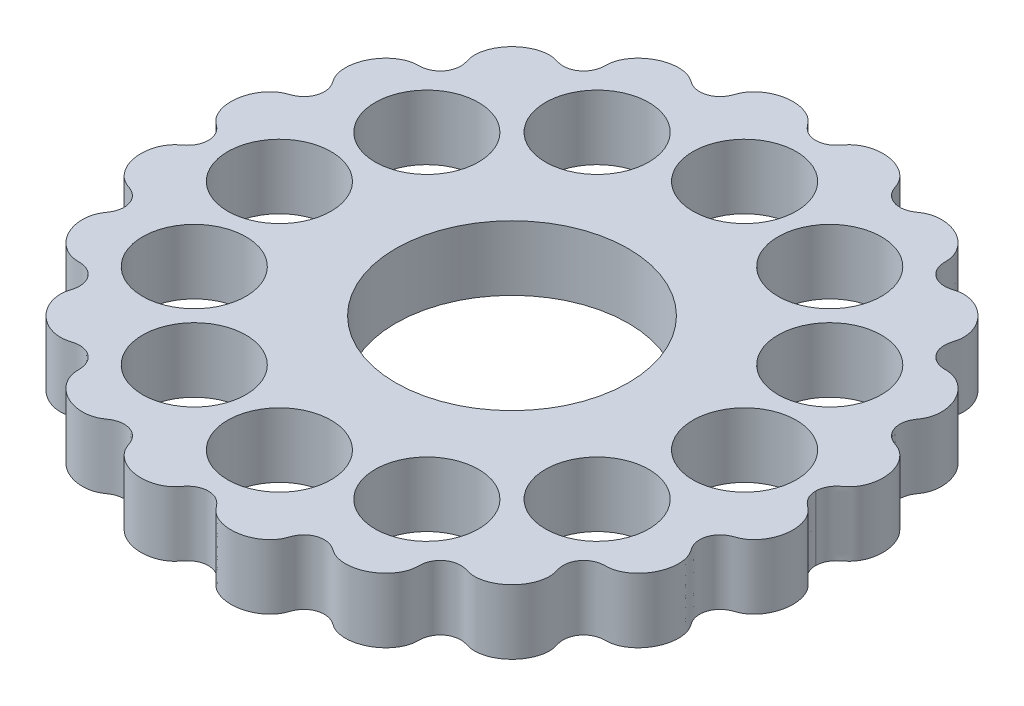
SolidWorks part; units mm, degrees
ref_plane "Front Plane" through (0, 0, 0) normal (0, 0, 1) x (1, 0, 0)
ref_plane "Top Plane" through (0, 0, 0) normal (0, 1, 0) x (1, 0, 0)
ref_plane "Right Plane" through (0, 0, 0) normal (1, 0, 0) x (0, 0, -1)
sketch "Sketch1" plane through (0, 0, 0) normal (0, 1, 0) x (1, 0, 0)
  line L0 (0, 0) -> (-50000, 0) construction
  line L1 (0, 0) -> (0, -50000) construction
  line L2 (23.5001, 0.0129) -> (23.5, 0)
  spline S0 degree 4 poles (21.8411, 12.6407) (22.0203, 12.5041) (22.35, 12.1932) (22.7473, 11.6384) (23.0173, 10.8905) (23.0906, 10.2173) (23.0371, 9.696) (22.9392, 9.3335) (22.8146, 9.0589) (22.692, 8.8679) (22.5629, 8.682) (22.419, 8.4431) (22.2854, 8.0962) (22.2414, 7.6218) (22.3709, 7.0968) (22.6485, 6.6795) (22.9702, 6.421) (23.2513, 6.2797) (23.4572, 6.2025) (23.6233, 6.1449) (23.8254, 6.0573) (24.0356, 5.9333) (24.2473, 5.7695) (24.502, 5.5171) (24.8314, 5.0866) (25.0873, 4.5396) (25.2302, 3.8953) (25.2334, 3.2499) (25.1572, 2.7564) (25.0153, 2.3299) (24.8302, 1.9758) (24.6224, 1.6961) (24.411, 1.4839) (24.1769, 1.3171) (23.9685, 1.1355) (23.7966, 0.9326) (23.6634, 0.7151) (23.5821, 0.5181) (23.5373, 0.3509) (23.5168, 0.2352) (23.5085, 0.1678) (23.5028, 0.0959) (23.4998, 0.0296) (23.4995, -0.0201) (23.5034, -0.114) (23.5136, -0.222) (23.531, -0.3171) (23.5554, -0.4164) (23.5855, -0.5129) (23.6209, -0.6076) (23.6842, -0.7456) (23.7985, -0.9357) (23.947, -1.1136) (24.1264, -1.2743) (24.3335, -1.4294) (24.5324, -1.5967) (24.7588, -1.8616) (24.9785, -2.239) (25.1878, -2.8156) (25.276, -3.602) (25.1512, -4.3864) (24.825, -5.1046) (24.4512, -5.5852) (24.1603, -5.8472) (23.9054, -6.0131) (23.7106, -6.1092) (23.5484, -6.1717) (23.3434, -6.2424) (23.1195, -6.3401) (22.8896, -6.4852) (22.6191, -6.7358) (22.3866, -7.0841) (22.2652, -7.485) (22.2642, -7.8967) (22.3323, -8.2005) (22.4106, -8.4063) (22.5009, -8.5801) (22.5924, -8.7259) (22.7163, -8.9012) (22.8496, -9.1231) (22.9784, -9.4447) (23.0662, -9.8699) (23.079, -10.3484) (23.0014, -10.8647) (22.7988, -11.4863) (22.4668, -12.0539) (22.0197, -12.5382) (21.5101, -12.8783) (21.1487, -13.0352) (20.8526, -13.1112) (20.6361, -13.1396) (20.4617, -13.1469) (20.2439, -13.1518) (19.9292, -13.1874) (19.5316, -13.3191) (19.1142, -13.6242) (18.8413, -14.0395) (18.7233, -14.4406) (18.7023, -14.7928) (18.731, -15.0474) (18.7862, -15.2675) (18.8561, -15.4948) (18.9091, -15.7274) (18.9298, -15.9928) (18.9132, -16.2851) (18.8535, -16.6269) (18.6921, -17.1381) (18.3245, -17.7837) (17.7439, -18.3557) (17.0924, -18.713) (16.5784, -18.8654) (16.2318, -18.9189) (15.9733, -18.9277) (15.7407, -18.9077) (15.5372, -18.8661) (15.3776, -18.8201) (15.1786, -18.7617) (14.943, -18.7144) (14.6698, -18.7015) (14.2938, -18.7551) (13.8912, -18.9202) (13.5591, -19.1968) (13.329, -19.5495) (13.2077, -19.8773) (13.1607, -20.1272) (13.1484, -20.3523) (13.1439, -20.5893) (13.1189, -20.8256) (13.0539, -21.0825) (12.9456, -21.3529) (12.7816, -21.6565) (12.4692, -22.0878) (11.918, -22.5852) (11.1862, -22.9469) (10.4524, -23.0817) (9.9115, -23.063) (9.5602, -23.002) (9.3067, -22.925) (9.0871, -22.8269) (8.8652, -22.6931) (8.6563, -22.5405) (8.4041, -22.4007) (8.1035, -22.3021) (7.7342, -22.2547) (7.3146, -22.3018) (6.9282, -22.4692) (6.6132, -22.7347) (6.426, -22.9803) (6.3196, -23.1695) (6.226, -23.3843) (6.1615, -23.5834) (6.0809, -23.7774) (5.9565, -23.9961) (5.784, -24.2355) (5.5184, -24.5091) (5.0388, -24.8605) (4.3152, -25.1707) (3.5217, -25.2796) (2.791, -25.1786) (2.2804, -24.9888) (1.9646, -24.8184) (1.7476, -24.6636) (1.57, -24.4991) (1.4301, -24.3329) (1.3258, -24.1944) (1.1879, -24.0267) (1.0116, -23.8555) (0.7865, -23.6977) (0.4445, -23.5448) (0.0278, -23.4694) (-0.3906, -23.5193) (-0.7681, -23.6831) (-1.0167, -23.8633) (-1.1726, -24.0123) (-1.2968, -24.1573) (-1.3971, -24.2895) (-1.5009, -24.4195) (-1.6153, -24.5403) (-1.7706, -24.6785) (-2.0089, -24.8488) (-2.3452, -25.0227) (-2.7867, -25.1648) (-3.2883, -25.2364) (-3.8051, -25.2271) (-4.3243, -25.1336) (-4.8311, -24.9525) (-5.2483, -24.7143) (-5.5687, -24.4567) (-5.8156, -24.1933) (-5.9728, -23.9761) (-6.0887, -23.762) (-6.1681, -23.5587) (-6.2249, -23.3939) (-6.3071, -23.1917) (-6.4261, -22.975) (-6.5967, -22.7573) (-6.8818, -22.5102) (-7.257, -22.3194) (-7.6664, -22.247) (-8.0669, -22.2913) (-8.3513, -22.3855) (-8.5443, -22.4795) (-8.7095, -22.5814) (-8.8513, -22.6808) (-9.0337, -22.7986) (-9.2686, -22.9122) (-9.5935, -23.0158) (-10.0105, -23.076) (-10.4681, -23.0671) (-10.9537, -22.977) (-11.5544, -22.765) (-12.1092, -22.4253) (-12.5378, -22.0129) (-12.8349, -21.57) (-12.9917, -21.2499) (-13.0792, -20.9957) (-13.1291, -20.7532) (-13.1456, -20.5281) (-13.1485, -20.348) (-13.1598, -20.1679) (-13.1871, -19.9893) (-13.2398, -19.7859) (-13.3301, -19.5635) (-13.5099, -19.2688) (-13.8217, -18.9659) (-14.2044, -18.7734) (-14.6123, -18.7018) (-14.9539, -18.7156) (-15.2392, -18.7725) (-15.5275, -18.8723) (-15.8439, -18.9245) (-16.211, -18.9262) (-16.6207, -18.8614) (-17.0591, -18.7152) (-17.5079, -18.4751) (-17.9196, -18.1609) (-18.2824, -17.7783) (-18.5826, -17.3336) (-18.777, -16.8971) (-18.8826, -16.5019) (-18.9258, -16.1458) (-18.9242, -15.8798) (-18.892, -15.6405) (-18.8254, -15.3899) (-18.7481, -15.1426) (-18.7014, -14.8514) (-18.7135, -14.5225) (-18.8073, -14.1364) (-18.9886, -13.8038) (-19.2393, -13.5373) (-19.5327, -13.3468) (-19.7706, -13.2423) (-20.0362, -13.1729) (-20.2842, -13.1482) (-20.5075, -13.1476) (-20.7449, -13.1288) (-20.9792, -13.0834) (-21.2878, -12.981) (-21.6535, -12.7906) (-22.1223, -12.4395) (-22.541, -11.9469) (-22.8516, -11.3681) (-23.0326, -10.7285) (-23.0802, -10.2504) (-23.0557, -9.8398) (-22.992, -9.529) (-22.9249, -9.3156) (-22.8467, -9.1329) (-22.7647, -8.9796) (-22.6446, -8.7988) (-22.4959, -8.5848) (-22.3648, -8.3186) (-22.2799, -7.9987) (-22.2576, -7.5993) (-22.3357, -7.227) (-22.4995, -6.8994) (-22.7252, -6.633) (-22.921, -6.4657) (-23.1192, -6.3437) (-23.3081, -6.2576) (-23.4795, -6.1951) (-23.6284, -6.1423) (-23.8097, -6.0641) (-24.0159, -5.9464) (-24.2743, -5.7519) (-24.5591, -5.4572) (-24.8912, -4.9791) (-25.1334, -4.3824) (-25.2472, -3.7364) (-25.2189, -3.0717) (-25.1135, -2.6002) (-24.9598, -2.2161) (-24.8002, -1.94) (-24.6679, -1.7581) (-24.5347, -1.6091) (-24.407, -1.4897) (-24.2694, -1.3823) (-24.1311, -1.2758) (-23.9675, -1.131) (-23.7997, -0.9408) (-23.6474, -0.695) (-23.5093, -0.3171) (-23.4729, 0.1074) (-23.5563, 0.5011) (-23.727, 0.8323) (-23.8894, 1.0456) (-24.0393, 1.199) (-24.2048, 1.3348) (-24.3765, 1.4623) (-24.5497, 1.6204) (-24.7146, 1.8141) (-24.8655, 2.0434) (-24.9966, 2.307) (-25.1232, 2.6524) (-25.2175, 3.0845) (-25.2518, 3.7039) (-25.1382, 4.3691) (-24.8937, 4.9741) (-24.5632, 5.452) (-24.2798, 5.7469) (-24.0225, 5.942) (-23.817, 6.0603) (-23.6362, 6.1392) (-23.4877, 6.1923) (-23.3164, 6.2542) (-23.1277, 6.3393) (-22.9293, 6.4598) (-22.733, 6.6253) (-22.5056, 6.8899) (-22.3394, 7.2164) (-22.2585, 7.5886) (-22.2783, 7.9889) (-22.3615, 8.31) (-22.4915, 8.5773) (-22.6398, 8.7922) (-22.7607, 8.9729) (-22.8435, 9.1261) (-22.9224, 9.3089) (-22.9904, 9.5224) (-23.0549, 9.8336) (-23.0804, 10.2449) (-23.0335, 10.724) (-22.8533, 11.364) (-22.5436, 11.943) (-22.1262, 12.4356) (-21.6591, 12.787) (-21.2947, 12.9779) (-20.9869, 13.0812) (-20.7533, 13.1275) (-20.5163, 13.1475) (-20.2934, 13.1479) (-20.0459, 13.1713) (-19.7806, 13.239) (-19.5426, 13.3415) (-19.248, 13.5298) (-18.9952, 13.7945) (-18.8114, 14.1263) (-18.7148, 14.5127) (-18.7008, 14.8421) (-18.7461, 15.1341) (-18.8228, 15.3821) (-18.8905, 15.6327) (-18.9237, 15.8723) (-18.9262, 16.1388) (-18.8839, 16.4957) (-18.779, 16.8918) (-18.585, 17.3295) (-18.285, 17.775) (-17.9228, 18.158) (-17.5119, 18.4724) (-17.0645, 18.7128) (-16.6274, 18.8596) (-16.2186, 18.9255) (-15.8523, 18.925) (-15.5361, 18.8747) (-15.2483, 18.7754) (-14.9641, 18.7169) (-14.6885, 18.7041) (-14.4289, 18.7338) (-14.0921, 18.8296) (-13.7745, 19.0104) (-13.5041, 19.274) (-13.301, 19.6135) (-13.1922, 19.9226) (-13.1499, 20.2133) (-13.1483, 20.4715) (-13.132, 20.7294) (-13.0869, 20.9657) (-13.0047, 21.2177) (-12.8523, 21.5409) (-12.5546, 21.9954) (-12.1223, 22.4164) (-11.5626, 22.7616) (-10.9582, 22.9757) (-10.4739, 23.0664) (-10.0172, 23.0763) (-9.601, 23.0174) (-9.2764, 22.9152) (-9.0416, 22.8028) (-8.859, 22.6861) (-8.7175, 22.5869) (-8.5532, 22.4845) (-8.3612, 22.3896) (-8.078, 22.2937) (-7.674, 22.246) (-7.258, 22.3178) (-6.875, 22.5132) (-6.5834, 22.7704) (-6.4109, 22.9973) (-6.2922, 23.2227) (-6.2111, 23.4323) (-6.1528, 23.6021) (-6.0658, 23.8096) (-5.9421, 24.0229) (-5.7795, 24.2358) (-5.5311, 24.4893) (-5.1118, 24.8155) (-4.5772, 25.0729) (-3.9447, 25.2227) (-3.3073, 25.2369) (-2.8158, 25.1705) (-2.3764, 25.0349) (-2.0369, 24.8654) (-1.7916, 24.6954) (-1.6273, 24.5522) (-1.5064, 24.4263) (-1.3975, 24.2901) (-1.2923, 24.1513) (-1.1647, 24.0039) (-1.0077, 23.8561) (-0.7627, 23.6813) (-0.3926, 23.5208) (0.0198, 23.4698) (0.4337, 23.5415) (0.7775, 23.6926) (1.004, 23.8492) (1.1816, 24.0198) (1.3204, 24.1873) (1.4248, 24.3261) (1.5642, 24.4931) (1.7414, 24.6587) (1.9584, 24.8145) (2.2742, 24.9862) (2.7855, 25.1775) (3.3895, 25.262) (4.055, 25.2066) (4.6806, 25.0138) (5.1366, 24.7881) (5.5131, 24.5135) (5.7789, 24.2413) (5.9519, 24.0032) (6.0559, 23.8218) (6.1261, 23.67) (6.1838, 23.513) (6.2393, 23.3556) (6.3148, 23.1792) (6.4198, 22.9898) (6.6049, 22.7433) (6.9178, 22.4755) (7.303, 22.305) (7.7226, 22.2547) (8.093, 22.2996) (8.3949, 22.3966) (8.6484, 22.5353) (8.8579, 22.6879) (9.0795, 22.8231) (9.2992, 22.9222) (9.5529, 23.0003) (9.9047, 23.0624) (10.4468, 23.0824) (11.0445, 22.9736) (11.6583, 22.7131) (12.1928, 22.3338) (12.5572, 21.9739) (12.8297, 21.592) (12.9966, 21.2469) (13.0848, 20.9637) (13.1336, 20.7153) (13.1478, 20.5046) (13.1482, 20.294) (13.1736, 20.0598) (13.2193, 19.8467) (13.3262, 19.5558) (13.553, 19.204) (13.882, 18.926) (14.2829, 18.7581) (14.6594, 18.702) (14.9333, 18.7133) (15.1696, 18.7594) (15.3691, 18.8175) (15.5288, 18.864) (15.7325, 18.9066) (15.9654, 18.9275) (16.2245, 18.9196) (16.5719, 18.867) (17.0874, 18.7154) (17.7398, 18.3589) (18.3213, 17.7878) (18.723, 17.0846) (18.8921, 16.4922) (18.9349, 16.0672) (18.9101, 15.7355) (18.8584, 15.5029) (18.7887, 15.2759) (18.7327, 15.0564) (18.7027, 14.8026) (18.7215, 14.4513) (18.8364, 14.05) (19.0669, 13.6933) (19.3919, 13.4205) (19.7259, 13.2551) (19.9902, 13.1813) (20.2348, 13.1524) (20.453, 13.147) (20.6277, 13.1403) (20.8446, 13.1128) (21.0781, 13.0539) (21.323, 12.9597) (21.6321, 12.7968) (22.0604, 12.4936) (22.553, 11.9616) (22.9181, 11.2563) (23.0818, 10.4848) (23.0669, 9.8769) (22.9806, 9.4523) (22.8531, 9.1307) (22.7213, 8.9085) (22.5727, 8.6983) (22.4484, 8.4944) (22.345, 8.2523) (22.2654, 7.9078) (22.2634, 7.4966) (22.3817, 7.0947) (22.6119, 6.7443) (22.8815, 6.4913) (23.1111, 6.3446) (23.335, 6.2456) (23.5402, 6.1745) (23.7028, 6.1126) (23.8984, 6.0172) (24.0996, 5.8873) (24.3006, 5.721) (24.5407, 5.4699) (24.7723, 5.1549) (24.9858, 4.7511) (25.1917, 4.1307) (25.2613, 3.4766) (25.1888, 2.8213) (24.9813, 2.2454) (24.7632, 1.8681) (24.5382, 1.6028) (24.3405, 1.4347) (24.1336, 1.2799) (23.9537, 1.1206) (23.8045, 0.9437) (23.6893, 0.7551) (23.6182, 0.6024) (23.5719, 0.4769) (23.5365, 0.3449) (23.5154, 0.2341) (23.5044, 0.1265) (23.4997, 0.0329) (23.4996, -0.0168) (23.502, -0.0831) (23.5072, -0.1552) (23.515, -0.2227) (23.5345, -0.3385) (23.578, -0.5062) (23.6578, -0.7037) (23.7892, -0.9224) (23.9596, -1.1262) (24.1387, -1.2851) (24.3097, -1.411) (24.481, -1.5549) (24.6365, -1.7161) (24.8235, -1.9651) (25.0104, -2.318) (25.1542, -2.744) (25.2324, -3.237) (25.2318, -3.8869) (25.0888, -4.5381) (24.8293, -5.0922) (24.4927, -5.5283) (24.2365, -5.7788) (24.0277, -5.9382) (23.8244, -6.0571) (23.6336, -6.1406) (23.4767, -6.1959) (23.2814, -6.2675) (23.002, -6.4009) (22.6719, -6.6524) (22.3818, -7.0679) (22.2423, -7.6006) (22.2819, -8.0803) (22.4122, -8.4287) (22.5543, -8.6688) (22.683, -8.8553) (22.8074, -9.0452) (22.9106, -9.2684) (22.9897, -9.5192) (23.0486, -9.8124) (23.0852, -10.2583) (23.0208, -10.8762) (22.7541, -11.6255) (22.359, -12.1823) (22.0307, -12.4947) (21.8521, -12.6323) knots 0 0 0 0 0 0.004253 0.008505 0.012712 0.014816 0.01692 0.018344 0.019769 0.020481 0.021194 0.022619 0.025024 0.027429 0.030028 0.032627 0.034286 0.035116 0.035945 0.036775 0.037604 0.039264 0.040537 0.041811 0.044358 0.049452 0.051797 0.054142 0.056487 0.058832 0.060238 0.061643 0.063049 0.064455 0.065652 0.06685 0.068047 0.069245 0.069666 0.070088 0.070299 0.07051 0.070932 0.07125 0.071568 0.072204 0.072839 0.073157 0.073475 0.074111 0.074747 0.076018 0.077648 0.078462 0.079277 0.080906 0.082536 0.085004 0.087473 0.09241 0.097302 0.099748 0.102194 0.103832 0.104651 0.105469 0.106288 0.107107 0.108745 0.110067 0.111388 0.114031 0.11655 0.11781 0.11907 0.119881 0.120692 0.121503 0.122314 0.123936 0.125558 0.12801 0.130462 0.132915 0.135367 0.14029 0.142752 0.145214 0.146859 0.147682 0.148505 0.149327 0.15015 0.151796 0.154462 0.157129 0.159695 0.160978 0.16226 0.163757 0.164505 0.165254 0.16675 0.168247 0.169507 0.170766 0.173285 0.178324 0.183363 0.185882 0.187142 0.188402 0.189968 0.190751 0.191534 0.192317 0.1931 0.194666 0.196057 0.197447 0.200228 0.202766 0.204035 0.205304 0.206795 0.20754 0.208286 0.209777 0.211268 0.212519 0.213771 0.216275 0.221281 0.226368 0.228911 0.230183 0.231455 0.233082 0.233896 0.234709 0.236336 0.237964 0.239304 0.240644 0.243325 0.245831 0.247083 0.248336 0.249126 0.249917 0.251497 0.252287 0.253078 0.254658 0.257053 0.259448 0.264238 0.269357 0.271917 0.273197 0.274477 0.276114 0.276932 0.277751 0.278569 0.279388 0.281025 0.282374 0.283723 0.28642 0.288913 0.290159 0.291406 0.29219 0.292973 0.293757 0.294541 0.295325 0.296109 0.297676 0.300056 0.302435 0.304815 0.307195 0.30977 0.312346 0.314922 0.31621 0.317498 0.319143 0.319966 0.320789 0.321612 0.322434 0.32408 0.325438 0.326797 0.329514 0.331921 0.333124 0.334327 0.335145 0.335963 0.336781 0.337599 0.339235 0.340871 0.343191 0.345511 0.347831 0.350151 0.355163 0.35767 0.358923 0.360176 0.361877 0.362727 0.363578 0.364428 0.365279 0.366129 0.36698 0.368387 0.369793 0.372606 0.375067 0.376297 0.377527 0.379032 0.380537 0.382042 0.383547 0.385937 0.388327 0.390718 0.393108 0.39567 0.398233 0.400795 0.402076 0.403357 0.404987 0.405802 0.406616 0.408246 0.409875 0.411331 0.412786 0.415696 0.416917 0.418138 0.419358 0.420579 0.422076 0.422824 0.423573 0.425069 0.426566 0.428941 0.431316 0.436065 0.438642 0.441219 0.443796 0.445084 0.446372 0.447191 0.44801 0.448829 0.449649 0.451287 0.452925 0.45439 0.455855 0.458784 0.459995 0.461205 0.462415 0.463625 0.46437 0.465114 0.465859 0.466604 0.468093 0.469583 0.471943 0.474303 0.479023 0.481613 0.484204 0.486795 0.48809 0.489385 0.490209 0.491032 0.491856 0.492679 0.493503 0.494326 0.495974 0.497448 0.498922 0.50187 0.503888 0.504897 0.505906 0.506915 0.507924 0.508933 0.509942 0.511328 0.512713 0.514099 0.515485 0.518256 0.521028 0.525738 0.528093 0.530448 0.531936 0.533423 0.534167 0.534911 0.535654 0.536398 0.537605 0.538811 0.540018 0.541224 0.54416 0.545628 0.547096 0.548737 0.550378 0.551198 0.552019 0.552839 0.55366 0.55495 0.556241 0.558822 0.561404 0.563985 0.568725 0.571095 0.573465 0.574959 0.576453 0.577201 0.577948 0.579442 0.580659 0.581877 0.583094 0.584311 0.587228 0.588687 0.590145 0.591777 0.59341 0.594226 0.595042 0.596674 0.597958 0.599241 0.601808 0.604375 0.606942 0.609328 0.611713 0.614098 0.616483 0.617986 0.619488 0.62099 0.622492 0.623719 0.624946 0.626174 0.627401 0.630298 0.631746 0.633195 0.634819 0.636442 0.637254 0.638066 0.63969 0.640967 0.642243 0.644795 0.6499 0.652215 0.65453 0.656845 0.659161 0.660793 0.662425 0.663242 0.664058 0.664874 0.66569 0.666891 0.668091 0.670492 0.673292 0.674692 0.676091 0.677787 0.678634 0.679482 0.680329 0.681177 0.682872 0.68412 0.685368 0.687864 0.692856 0.695186 0.697517 0.699847 0.702177 0.703821 0.704643 0.705464 0.706286 0.707108 0.70793 0.708752 0.70996 0.711169 0.713586 0.71629 0.717642 0.718994 0.720633 0.721453 0.722273 0.723093 0.723913 0.725553 0.726835 0.728118 0.730683 0.735813 0.738203 0.740593 0.742983 0.745373 0.746949 0.747737 0.748525 0.749313 0.750101 0.750889 0.751677 0.752928 0.754179 0.756681 0.759367 0.76071 0.762053 0.763683 0.765314 0.766129 0.766944 0.768574 0.769849 0.771123 0.773672 0.778769 0.781175 0.78358 0.785985 0.788391 0.789981 0.790776 0.791571 0.793161 0.793956 0.794751 0.796007 0.797264 0.799777 0.802564 0.803958 0.805352 0.806921 0.807705 0.80849 0.809274 0.810059 0.811628 0.81289 0.814152 0.816677 0.821726 0.826754 0.829268 0.831782 0.833277 0.834772 0.835519 0.836267 0.837761 0.83904 0.840318 0.842875 0.845549 0.846886 0.848223 0.849872 0.850696 0.85152 0.852344 0.853168 0.854816 0.856049 0.857283 0.859749 0.864683 0.869577 0.872024 0.874471 0.876091 0.87771 0.87852 0.87933 0.88095 0.882206 0.883462 0.885973 0.888624 0.889949 0.891274 0.892915 0.893735 0.894555 0.895375 0.896195 0.897836 0.899061 0.900287 0.902738 0.905189 0.90764 0.912566 0.91503 0.917493 0.91912 0.920747 0.92156 0.922374 0.924001 0.925269 0.925903 0.926536 0.92717 0.927804 0.928438 0.928755 0.929072 0.929494 0.929706 0.929917 0.930339 0.930762 0.931959 0.933156 0.934353 0.93555 0.936956 0.937659 0.938362 0.939767 0.941173 0.943518 0.945863 0.948208 0.950553 0.955729 0.958318 0.959612 0.960906 0.962476 0.96326 0.964045 0.96483 0.965615 0.967185 0.969873 0.972561 0.974966 0.977371 0.978797 0.97951 0.980223 0.981649 0.983075 0.984127 0.985179 0.987283 0.991492 0.995746 1 1 1 1 1 construction
  spline S1 degree 4 poles (23.5, 0) (23.5, -0.0145) (23.5005, -0.0435) (23.5034, -0.114) (23.5136, -0.222) (23.531, -0.3171) (23.5554, -0.4164) (23.5855, -0.5129) (23.6209, -0.6076) (23.6842, -0.7456) (23.7985, -0.9357) (23.947, -1.1136) (24.1264, -1.2743) (24.3335, -1.4294) (24.5324, -1.5967) (24.7588, -1.8616) (24.9785, -2.239) (25.1878, -2.8156) (25.276, -3.602) (25.1512, -4.3864) (24.825, -5.1046) (24.4512, -5.5852) (24.1603, -5.8472) (23.9054, -6.0131) (23.7106, -6.1092) (23.5484, -6.1717) (23.3434, -6.2424) (23.1195, -6.3401) (22.8896, -6.4852) (22.6191, -6.7358) (22.3866, -7.0841) (22.2652, -7.485) (22.2642, -7.8967) (22.3323, -8.2005) (22.4106, -8.4063) (22.5009, -8.5801) (22.5924, -8.7259) (22.7163, -8.9012) (22.8496, -9.1231) (22.9784, -9.4447) (23.0662, -9.8699) (23.079, -10.3484) (23.0014, -10.8647) (22.7988, -11.4863) (22.4668, -12.0539) (22.0197, -12.5382) (21.5101, -12.8783) (21.1487, -13.0352) (20.8526, -13.1112) (20.6361, -13.1396) (20.4617, -13.1469) (20.2439, -13.1518) (19.9292, -13.1874) (19.5316, -13.3191) (19.1142, -13.6242) (18.8413, -14.0395) (18.7233, -14.4406) (18.7023, -14.7928) (18.731, -15.0474) (18.7862, -15.2675) (18.8561, -15.4948) (18.9091, -15.7274) (18.9298, -15.9928) (18.9132, -16.2851) (18.8535, -16.6269) (18.6921, -17.1381) (18.3245, -17.7837) (17.7439, -18.3557) (17.0924, -18.713) (16.5784, -18.8654) (16.2318, -18.9189) (15.9733, -18.9277) (15.7407, -18.9077) (15.5372, -18.8661) (15.3776, -18.8201) (15.1786, -18.7617) (14.943, -18.7144) (14.6698, -18.7015) (14.2938, -18.7551) (13.8912, -18.9202) (13.5591, -19.1968) (13.329, -19.5495) (13.2077, -19.8773) (13.1607, -20.1272) (13.1484, -20.3523) (13.1439, -20.5893) (13.1189, -20.8256) (13.0539, -21.0825) (12.9456, -21.3529) (12.7816, -21.6565) (12.4692, -22.0878) (11.918, -22.5852) (11.1862, -22.9469) (10.4524, -23.0817) (9.9115, -23.063) (9.5602, -23.002) (9.3067, -22.925) (9.0871, -22.8269) (8.8652, -22.6931) (8.6563, -22.5405) (8.4041, -22.4007) (8.1035, -22.3021) (7.7342, -22.2547) (7.3146, -22.3018) (6.9282, -22.4692) (6.6132, -22.7347) (6.426, -22.9803) (6.3196, -23.1695) (6.226, -23.3843) (6.1615, -23.5834) (6.0809, -23.7774) (5.9565, -23.9961) (5.784, -24.2355) (5.5184, -24.5091) (5.0388, -24.8605) (4.3152, -25.1707) (3.5217, -25.2796) (2.791, -25.1786) (2.2804, -24.9888) (1.9646, -24.8184) (1.7476, -24.6636) (1.57, -24.4991) (1.4301, -24.3329) (1.3258, -24.1944) (1.1879, -24.0267) (1.0116, -23.8555) (0.7865, -23.6977) (0.4445, -23.5448) (0.0278, -23.4694) (-0.3906, -23.5193) (-0.7681, -23.6831) (-1.0167, -23.8633) (-1.1726, -24.0123) (-1.2968, -24.1573) (-1.3971, -24.2895) (-1.5009, -24.4195) (-1.6153, -24.5403) (-1.7706, -24.6785) (-2.0089, -24.8488) (-2.3452, -25.0227) (-2.7867, -25.1648) (-3.2883, -25.2364) (-3.8051, -25.2271) (-4.3243, -25.1336) (-4.8311, -24.9525) (-5.2483, -24.7143) (-5.5687, -24.4567) (-5.8156, -24.1933) (-5.9728, -23.9761) (-6.0887, -23.762) (-6.1681, -23.5587) (-6.2249, -23.3939) (-6.3071, -23.1917) (-6.4261, -22.975) (-6.5967, -22.7573) (-6.8818, -22.5102) (-7.257, -22.3194) (-7.6664, -22.247) (-8.0669, -22.2913) (-8.3513, -22.3855) (-8.5443, -22.4795) (-8.7095, -22.5814) (-8.8513, -22.6808) (-9.0337, -22.7986) (-9.2686, -22.9122) (-9.5935, -23.0158) (-10.0105, -23.076) (-10.4681, -23.0671) (-10.9537, -22.977) (-11.5544, -22.765) (-12.1092, -22.4253) (-12.5378, -22.0129) (-12.8349, -21.57) (-12.9917, -21.2499) (-13.0792, -20.9957) (-13.1291, -20.7532) (-13.1456, -20.5281) (-13.1485, -20.348) (-13.1598, -20.1679) (-13.1871, -19.9893) (-13.2398, -19.7859) (-13.3301, -19.5635) (-13.5099, -19.2688) (-13.8217, -18.9659) (-14.2044, -18.7734) (-14.6123, -18.7018) (-14.9539, -18.7156) (-15.2392, -18.7725) (-15.5275, -18.8723) (-15.8439, -18.9245) (-16.211, -18.9262) (-16.6207, -18.8614) (-17.0591, -18.7152) (-17.5079, -18.4751) (-17.9196, -18.1609) (-18.2824, -17.7783) (-18.5826, -17.3336) (-18.777, -16.8971) (-18.8826, -16.5019) (-18.9258, -16.1458) (-18.9242, -15.8798) (-18.892, -15.6405) (-18.8254, -15.3899) (-18.7481, -15.1426) (-18.7014, -14.8514) (-18.7135, -14.5225) (-18.8073, -14.1364) (-18.9886, -13.8038) (-19.2393, -13.5373) (-19.5327, -13.3468) (-19.7706, -13.2423) (-20.0362, -13.1729) (-20.2842, -13.1482) (-20.5075, -13.1476) (-20.7449, -13.1288) (-20.9792, -13.0834) (-21.2878, -12.981) (-21.6535, -12.7906) (-22.1223, -12.4395) (-22.541, -11.9469) (-22.8516, -11.3681) (-23.0326, -10.7285) (-23.0802, -10.2504) (-23.0557, -9.8398) (-22.992, -9.529) (-22.9249, -9.3156) (-22.8467, -9.1329) (-22.7647, -8.9796) (-22.6446, -8.7988) (-22.4959, -8.5848) (-22.3648, -8.3186) (-22.2799, -7.9987) (-22.2576, -7.5993) (-22.3357, -7.227) (-22.4995, -6.8994) (-22.7252, -6.633) (-22.921, -6.4657) (-23.1192, -6.3437) (-23.3081, -6.2576) (-23.4795, -6.1951) (-23.6284, -6.1423) (-23.8097, -6.0641) (-24.0159, -5.9464) (-24.2743, -5.7519) (-24.5591, -5.4572) (-24.8912, -4.9791) (-25.1334, -4.3824) (-25.2472, -3.7364) (-25.2189, -3.0717) (-25.1135, -2.6002) (-24.9598, -2.2161) (-24.8002, -1.94) (-24.6679, -1.7581) (-24.5347, -1.6091) (-24.407, -1.4897) (-24.2694, -1.3823) (-24.1311, -1.2758) (-23.9675, -1.131) (-23.7997, -0.9408) (-23.6474, -0.695) (-23.5093, -0.3171) (-23.4729, 0.1074) (-23.5563, 0.5011) (-23.727, 0.8323) (-23.8894, 1.0456) (-24.0393, 1.199) (-24.2048, 1.3348) (-24.3765, 1.4623) (-24.5497, 1.6204) (-24.7146, 1.8141) (-24.8655, 2.0434) (-24.9966, 2.307) (-25.1232, 2.6524) (-25.2175, 3.0845) (-25.2518, 3.7039) (-25.1382, 4.3691) (-24.8937, 4.9741) (-24.5632, 5.452) (-24.2798, 5.7469) (-24.0225, 5.942) (-23.817, 6.0603) (-23.6362, 6.1392) (-23.4877, 6.1923) (-23.3164, 6.2542) (-23.1277, 6.3393) (-22.9293, 6.4598) (-22.733, 6.6253) (-22.5056, 6.8899) (-22.3394, 7.2164) (-22.2585, 7.5886) (-22.2783, 7.9889) (-22.3615, 8.31) (-22.4915, 8.5773) (-22.6398, 8.7922) (-22.7607, 8.9729) (-22.8435, 9.1261) (-22.9224, 9.3089) (-22.9904, 9.5224) (-23.0549, 9.8336) (-23.0804, 10.2449) (-23.0335, 10.724) (-22.8533, 11.364) (-22.5436, 11.943) (-22.1262, 12.4356) (-21.6591, 12.787) (-21.2947, 12.9779) (-20.9869, 13.0812) (-20.7533, 13.1275) (-20.5163, 13.1475) (-20.2934, 13.1479) (-20.0459, 13.1713) (-19.7806, 13.239) (-19.5426, 13.3415) (-19.248, 13.5298) (-18.9952, 13.7945) (-18.8114, 14.1263) (-18.7148, 14.5127) (-18.7008, 14.8421) (-18.7461, 15.1341) (-18.8228, 15.3821) (-18.8905, 15.6327) (-18.9237, 15.8723) (-18.9262, 16.1388) (-18.8839, 16.4957) (-18.779, 16.8918) (-18.585, 17.3295) (-18.285, 17.775) (-17.9228, 18.158) (-17.5119, 18.4724) (-17.0645, 18.7128) (-16.6274, 18.8596) (-16.2186, 18.9255) (-15.8523, 18.925) (-15.5361, 18.8747) (-15.2483, 18.7754) (-14.9641, 18.7169) (-14.6885, 18.7041) (-14.4289, 18.7338) (-14.0921, 18.8296) (-13.7745, 19.0104) (-13.5041, 19.274) (-13.301, 19.6135) (-13.1922, 19.9226) (-13.1499, 20.2133) (-13.1483, 20.4715) (-13.132, 20.7294) (-13.0869, 20.9657) (-13.0047, 21.2177) (-12.8523, 21.5409) (-12.5546, 21.9954) (-12.1223, 22.4164) (-11.5626, 22.7616) (-10.9582, 22.9757) (-10.4739, 23.0664) (-10.0172, 23.0763) (-9.601, 23.0174) (-9.2764, 22.9152) (-9.0416, 22.8028) (-8.859, 22.6861) (-8.7175, 22.5869) (-8.5532, 22.4845) (-8.3612, 22.3896) (-8.078, 22.2937) (-7.674, 22.246) (-7.258, 22.3178) (-6.875, 22.5132) (-6.5834, 22.7704) (-6.4109, 22.9973) (-6.2922, 23.2227) (-6.2111, 23.4323) (-6.1528, 23.6021) (-6.0658, 23.8096) (-5.9421, 24.0229) (-5.7795, 24.2358) (-5.5311, 24.4893) (-5.1118, 24.8155) (-4.5772, 25.0729) (-3.9447, 25.2227) (-3.3073, 25.2369) (-2.8158, 25.1705) (-2.3764, 25.0349) (-2.0369, 24.8654) (-1.7916, 24.6954) (-1.6273, 24.5522) (-1.5064, 24.4263) (-1.3975, 24.2901) (-1.2923, 24.1513) (-1.1647, 24.0039) (-1.0077, 23.8561) (-0.7627, 23.6813) (-0.3926, 23.5208) (0.0198, 23.4698) (0.4337, 23.5415) (0.7775, 23.6926) (1.004, 23.8492) (1.1816, 24.0198) (1.3204, 24.1873) (1.4248, 24.3261) (1.5642, 24.4931) (1.7414, 24.6587) (1.9584, 24.8145) (2.2742, 24.9862) (2.7855, 25.1775) (3.3895, 25.262) (4.055, 25.2066) (4.6806, 25.0138) (5.1366, 24.7881) (5.5131, 24.5135) (5.7789, 24.2413) (5.9519, 24.0032) (6.0559, 23.8218) (6.1261, 23.67) (6.1838, 23.513) (6.2393, 23.3556) (6.3148, 23.1792) (6.4198, 22.9898) (6.6049, 22.7433) (6.9178, 22.4755) (7.303, 22.305) (7.7226, 22.2547) (8.093, 22.2996) (8.3949, 22.3966) (8.6484, 22.5353) (8.8579, 22.6879) (9.0795, 22.8231) (9.2992, 22.9222) (9.5529, 23.0003) (9.9047, 23.0624) (10.4468, 23.0824) (11.0445, 22.9736) (11.6583, 22.7131) (12.1928, 22.3338) (12.5572, 21.9739) (12.8297, 21.592) (12.9966, 21.2469) (13.0848, 20.9637) (13.1336, 20.7153) (13.1478, 20.5046) (13.1482, 20.294) (13.1736, 20.0598) (13.2193, 19.8467) (13.3262, 19.5558) (13.553, 19.204) (13.882, 18.926) (14.2829, 18.7581) (14.6594, 18.702) (14.9333, 18.7133) (15.1696, 18.7594) (15.3691, 18.8175) (15.5288, 18.864) (15.7325, 18.9066) (15.9654, 18.9275) (16.2245, 18.9196) (16.5719, 18.867) (17.0874, 18.7154) (17.7398, 18.3589) (18.3213, 17.7878) (18.723, 17.0846) (18.8921, 16.4922) (18.9349, 16.0672) (18.9101, 15.7355) (18.8584, 15.5029) (18.7887, 15.2759) (18.7327, 15.0564) (18.7027, 14.8026) (18.7215, 14.4513) (18.8364, 14.05) (19.0669, 13.6933) (19.3919, 13.4205) (19.7259, 13.2551) (19.9902, 13.1813) (20.2348, 13.1524) (20.453, 13.147) (20.6277, 13.1403) (20.8446, 13.1128) (21.0781, 13.0539) (21.323, 12.9597) (21.6321, 12.7968) (22.0604, 12.4936) (22.553, 11.9616) (22.9181, 11.2563) (23.0818, 10.4848) (23.0669, 9.8769) (22.9806, 9.4523) (22.8531, 9.1307) (22.7213, 8.9085) (22.5727, 8.6983) (22.4484, 8.4944) (22.345, 8.2523) (22.2654, 7.9078) (22.2634, 7.4966) (22.3817, 7.0947) (22.6119, 6.7443) (22.8815, 6.4913) (23.1111, 6.3446) (23.335, 6.2456) (23.5402, 6.1745) (23.7028, 6.1126) (23.8984, 6.0172) (24.0996, 5.8873) (24.3006, 5.721) (24.5407, 5.4699) (24.7723, 5.1549) (24.9858, 4.7511) (25.1917, 4.1307) (25.2613, 3.4766) (25.1888, 2.8213) (24.9813, 2.2454) (24.7632, 1.8681) (24.5382, 1.6028) (24.3405, 1.4347) (24.1336, 1.2799) (23.9537, 1.1206) (23.8045, 0.9437) (23.6893, 0.7551) (23.6182, 0.6024) (23.5719, 0.4769) (23.5365, 0.3449) (23.5154, 0.2341) (23.5044, 0.1265) (23.5009, 0.0563) (23.5002, 0.0274) (23.5001, 0.0129) knots 0.070932 0.070932 0.070932 0.070932 0.070932 0.07125 0.071568 0.072204 0.072839 0.073157 0.073475 0.074111 0.074747 0.076018 0.077648 0.078462 0.079277 0.080906 0.082536 0.085004 0.087473 0.09241 0.097302 0.099748 0.102194 0.103832 0.104651 0.105469 0.106288 0.107107 0.108745 0.110067 0.111388 0.114031 0.11655 0.11781 0.11907 0.119881 0.120692 0.121503 0.122314 0.123936 0.125558 0.12801 0.130462 0.132915 0.135367 0.14029 0.142752 0.145214 0.146859 0.147682 0.148505 0.149327 0.15015 0.151796 0.154462 0.157129 0.159695 0.160978 0.16226 0.163757 0.164505 0.165254 0.16675 0.168247 0.169507 0.170766 0.173285 0.178324 0.183363 0.185882 0.187142 0.188402 0.189968 0.190751 0.191534 0.192317 0.1931 0.194666 0.196057 0.197447 0.200228 0.202766 0.204035 0.205304 0.206795 0.20754 0.208286 0.209777 0.211268 0.212519 0.213771 0.216275 0.221281 0.226368 0.228911 0.230183 0.231455 0.233082 0.233896 0.234709 0.236336 0.237964 0.239304 0.240644 0.243325 0.245831 0.247083 0.248336 0.249126 0.249917 0.251497 0.252287 0.253078 0.254658 0.257053 0.259448 0.264238 0.269357 0.271917 0.273197 0.274477 0.276114 0.276932 0.277751 0.278569 0.279388 0.281025 0.282374 0.283723 0.28642 0.288913 0.290159 0.291406 0.29219 0.292973 0.293757 0.294541 0.295325 0.296109 0.297676 0.300056 0.302435 0.304815 0.307195 0.30977 0.312346 0.314922 0.31621 0.317498 0.319143 0.319966 0.320789 0.321612 0.322434 0.32408 0.325438 0.326797 0.329514 0.331921 0.333124 0.334327 0.335145 0.335963 0.336781 0.337599 0.339235 0.340871 0.343191 0.345511 0.347831 0.350151 0.355163 0.35767 0.358923 0.360176 0.361877 0.362727 0.363578 0.364428 0.365279 0.366129 0.36698 0.368387 0.369793 0.372606 0.375067 0.376297 0.377527 0.379032 0.380537 0.382042 0.383547 0.385937 0.388327 0.390718 0.393108 0.39567 0.398233 0.400795 0.402076 0.403357 0.404987 0.405802 0.406616 0.408246 0.409875 0.411331 0.412786 0.415696 0.416917 0.418138 0.419358 0.420579 0.422076 0.422824 0.423573 0.425069 0.426566 0.428941 0.431316 0.436065 0.438642 0.441219 0.443796 0.445084 0.446372 0.447191 0.44801 0.448829 0.449649 0.451287 0.452925 0.45439 0.455855 0.458784 0.459995 0.461205 0.462415 0.463625 0.46437 0.465114 0.465859 0.466604 0.468093 0.469583 0.471943 0.474303 0.479023 0.481613 0.484204 0.486795 0.48809 0.489385 0.490209 0.491032 0.491856 0.492679 0.493503 0.494326 0.495974 0.497448 0.498922 0.50187 0.503888 0.504897 0.505906 0.506915 0.507924 0.508933 0.509942 0.511328 0.512713 0.514099 0.515485 0.518256 0.521028 0.525738 0.528093 0.530448 0.531936 0.533423 0.534167 0.534911 0.535654 0.536398 0.537605 0.538811 0.540018 0.541224 0.54416 0.545628 0.547096 0.548737 0.550378 0.551198 0.552019 0.552839 0.55366 0.55495 0.556241 0.558822 0.561404 0.563985 0.568725 0.571095 0.573465 0.574959 0.576453 0.577201 0.577948 0.579442 0.580659 0.581877 0.583094 0.584311 0.587228 0.588687 0.590145 0.591777 0.59341 0.594226 0.595042 0.596674 0.597958 0.599241 0.601808 0.604375 0.606942 0.609328 0.611713 0.614098 0.616483 0.617986 0.619488 0.62099 0.622492 0.623719 0.624946 0.626174 0.627401 0.630298 0.631746 0.633195 0.634819 0.636442 0.637254 0.638066 0.63969 0.640967 0.642243 0.644795 0.6499 0.652215 0.65453 0.656845 0.659161 0.660793 0.662425 0.663242 0.664058 0.664874 0.66569 0.666891 0.668091 0.670492 0.673292 0.674692 0.676091 0.677787 0.678634 0.679482 0.680329 0.681177 0.682872 0.68412 0.685368 0.687864 0.692856 0.695186 0.697517 0.699847 0.702177 0.703821 0.704643 0.705464 0.706286 0.707108 0.70793 0.708752 0.70996 0.711169 0.713586 0.71629 0.717642 0.718994 0.720633 0.721453 0.722273 0.723093 0.723913 0.725553 0.726835 0.728118 0.730683 0.735813 0.738203 0.740593 0.742983 0.745373 0.746949 0.747737 0.748525 0.749313 0.750101 0.750889 0.751677 0.752928 0.754179 0.756681 0.759367 0.76071 0.762053 0.763683 0.765314 0.766129 0.766944 0.768574 0.769849 0.771123 0.773672 0.778769 0.781175 0.78358 0.785985 0.788391 0.789981 0.790776 0.791571 0.793161 0.793956 0.794751 0.796007 0.797264 0.799777 0.802564 0.803958 0.805352 0.806921 0.807705 0.80849 0.809274 0.810059 0.811628 0.81289 0.814152 0.816677 0.821726 0.826754 0.829268 0.831782 0.833277 0.834772 0.835519 0.836267 0.837761 0.83904 0.840318 0.842875 0.845549 0.846886 0.848223 0.849872 0.850696 0.85152 0.852344 0.853168 0.854816 0.856049 0.857283 0.859749 0.864683 0.869577 0.872024 0.874471 0.876091 0.87771 0.87852 0.87933 0.88095 0.882206 0.883462 0.885973 0.888624 0.889949 0.891274 0.892915 0.893735 0.894555 0.895375 0.896195 0.897836 0.899061 0.900287 0.902738 0.905189 0.90764 0.912566 0.91503 0.917493 0.91912 0.920747 0.92156 0.922374 0.924001 0.925269 0.925903 0.926536 0.92717 0.927804 0.928438 0.928755 0.929072 0.929072 0.929072 0.929072 0.929072
extrude "Boss-Extrude1" add sketch "Sketch1" along normal blind 5
sketch "Sketch2" plane through (0, 5, 0) normal (0, 1, 0) x (1, 0, 0)
  line L0 (0, 0) -> (-50000, 0) construction
  line L1 (0, 0) -> (0, -50000) construction
  circle A0 centre (0, 0) radius 9
  dimension "D1" = 18
extrude "Cut-Extrude1" cut sketch "Sketch2" against normal through all
sketch "Sketch3" plane through (0, 5, 0) normal (0, 1, 0) x (1, 0, 0)
  line L0 (0, 0) -> (-50000, 0) construction
  line L1 (0, 0) -> (0, -50000) construction
  circle A1 centre (0, 0) radius 10.5 construction
  circle A2 centre (0, 0) radius 18 construction
  circle A3 centre (-18, 0) radius 4
  circle A4 centre (-15.5885, 9) radius 4
  circle A5 centre (-9, 15.5885) radius 4
  circle A6 centre (0, 18) radius 4
  circle A7 centre (9, 15.5885) radius 4
  circle A8 centre (15.5885, 9) radius 4
  circle A9 centre (0, 0) radius 25.5 construction
  circle A10 centre (18, 0) radius 4
  circle A11 centre (15.5885, -9) radius 4
  circle A12 centre (9, -15.5885) radius 4
  circle A13 centre (0, -18) radius 4
  circle A14 centre (-9, -15.5885) radius 4
  circle A15 centre (-15.5885, -9) radius 4
  point P24 (0, 0)
  dimension "D2" = 21
  dimension "D3" = 36
  dimension "D4" = 8
  dimension "D6" = 51
  dimension "D5" = 12
extrude "Cut-Extrude2" cut sketch "Sketch3" against normal through all
